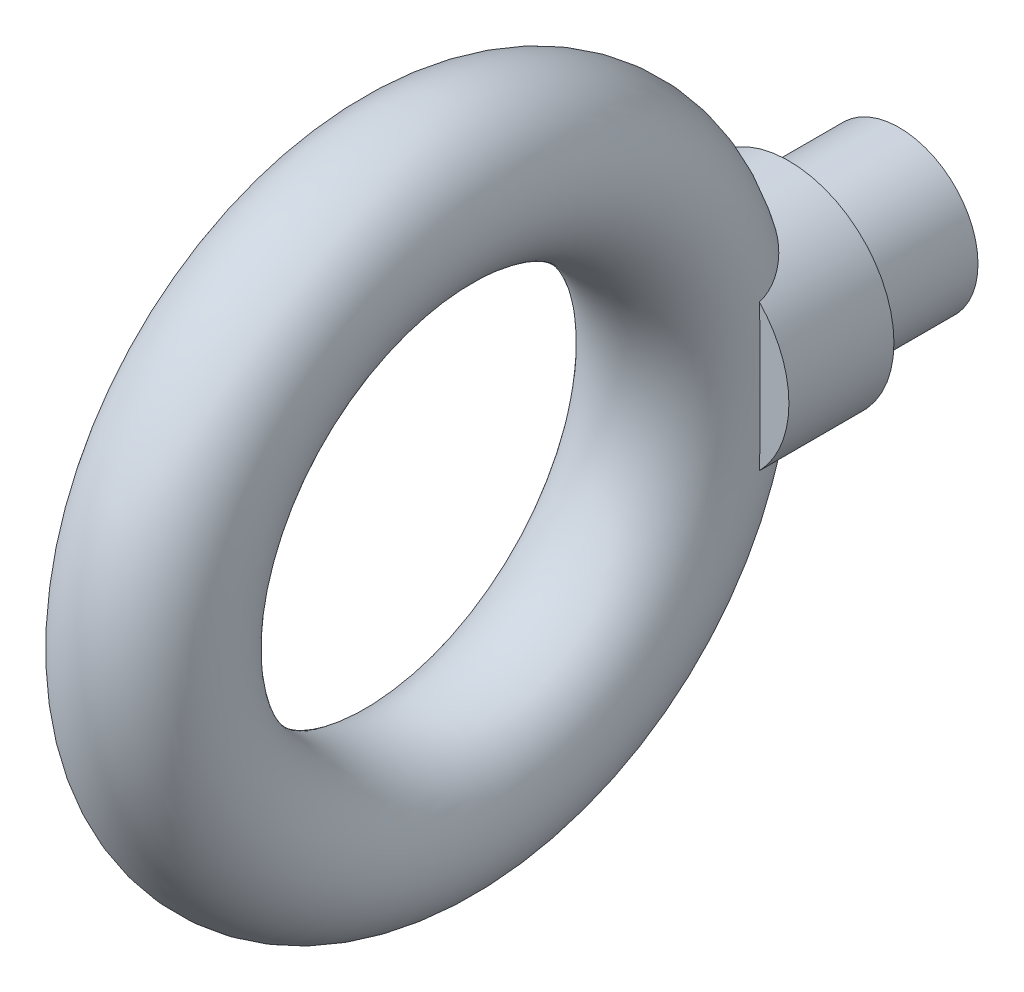
SolidWorks part; units mm, degrees
ref_plane "正面" through (0, 0, 0) normal (0, 0, 1) x (1, 0, 0)
ref_plane "平面" through (0, 0, 0) normal (0, 1, 0) x (1, 0, 0)
ref_plane "右側面" through (0, 0, 0) normal (1, 0, 0) x (0, 0, -1)
sketch "ｽｹｯﾁ1" plane through (0, 0, 0) normal (0, 0, 1) x (1, 0, 0)
  circle A0 centre (0, 0) radius 3
  dimension "D1" = 6
extrude "ﾎﾞｽ - 押し出し1" add sketch "ｽｹｯﾁ1" along normal blind 8.2
cosmetic thread "ねじ山1" parameters "D1"=4.2, "D2"=5
sketch "ｽｹｯﾁ2" plane through (0, 0, 0) normal (1, 0, 0) x (0, 0, -1)
  line L0 (-8.2, 3) -> (-8.2, -3) construction
  circle A0 centre (-18.3, 0) radius 10.1
  dimension "D1" = 20.2
sketch "ｽｹｯﾁ3" plane through (0, 0, 0) normal (0, 1, 0) x (1, 0, 0)
  line L0 (-3, -8.2) -> (3, -8.2) construction
  circle A0 centre (0, -8.2) radius 2.9
  dimension "D1" = 5.8
sweep "ｽｲｰﾌﾟ1" add profiles "ｽｹｯﾁ3" path "ｽｹｯﾁ2"
sketch "ｽｹｯﾁ4" plane through (0, 0, 8.2) normal (0, 0, 1) x (1, 0, 0)
  circle A0 centre (0, 0) radius 4
extrude "ﾎﾞｽ - 押し出し2" add sketch "ｽｹｯﾁ4" against normal blind 4
sketch3d "3Dｽｹｯﾁ1"
  point P0 (0, 0, 11.1)
